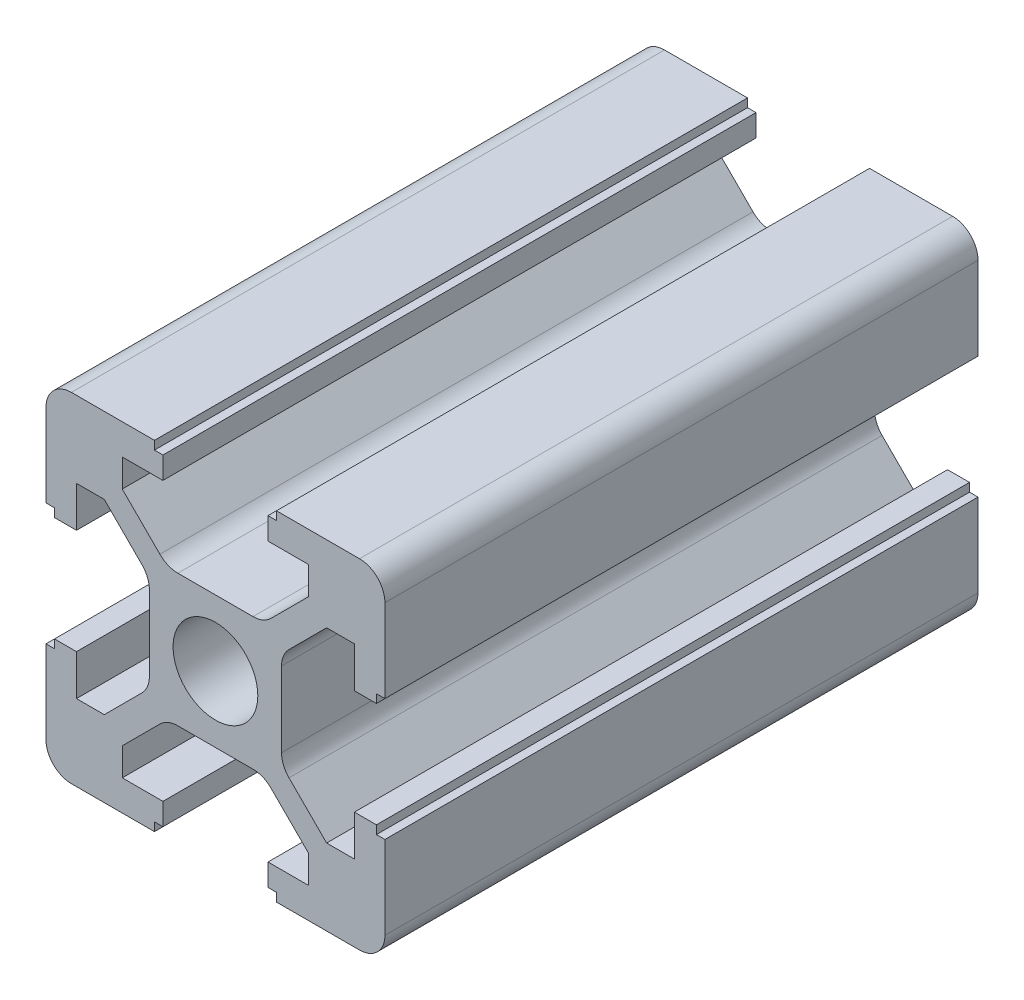
SolidWorks part; units mm, degrees
material "6061 合金"
ref_plane "前视基准面" through (0, 0, 0) normal (0, 0, 1) x (1, 0, 0)
ref_plane "上视基准面" through (0, 0, 0) normal (0, 1, 0) x (1, 0, 0)
ref_plane "右视基准面" through (0, 0, 0) normal (1, 0, 0) x (0, 0, -1)
sketch "草图1" plane through (0, 0, 0) normal (0, 0, 1) x (1, 0, 0)
  line L0 (-6.5607, 5.5) -> (-4.3393, 3.2787)
  line L1 (-3.9, 2.218) -> (-3.9, -2.218)
  line L2 (-4.3393, -3.2787) -> (-6.5607, -5.5)
  line L3 (-6.5607, -5.5) -> (-8.2, -5.5)
  line L4 (-8.2, -5.5) -> (-8.2, -3.1)
  line L5 (-8.2, -3.1) -> (-9.5, -3.1)
  line L6 (-9.5, -3.1) -> (-9.5, -3.6)
  line L7 (-9.5, -3.6) -> (-10, -3.6)
  line L8 (-10, -3.6) -> (-10, -8.5)
  line L9 (-6.5607, 5.5) -> (-8.2, 5.5)
  line L10 (-8.2, 5.5) -> (-8.2, 3.1)
  line L11 (-8.2, 3.1) -> (-9.5, 3.1)
  line L12 (-9.5, 3.1) -> (-9.5, 3.6)
  line L13 (-9.5, 3.6) -> (-10, 3.6)
  line L14 (-10, 3.6) -> (-10, 8.5)
  line L15 (5.5, 6.5607) -> (3.2787, 4.3393)
  line L16 (2.218, 3.9) -> (-2.218, 3.9)
  line L17 (-3.2787, 4.3393) -> (-5.5, 6.5607)
  line L18 (-5.5, 6.5607) -> (-5.5, 8.2)
  line L19 (-5.5, 8.2) -> (-3.1, 8.2)
  line L20 (-3.1, 8.2) -> (-3.1, 9.5)
  line L21 (-3.1, 9.5) -> (-3.6, 9.5)
  line L22 (-3.6, 9.5) -> (-3.6, 10)
  line L23 (-3.6, 10) -> (-8.5, 10)
  line L24 (5.5, 6.5607) -> (5.5, 8.2)
  line L25 (5.5, 8.2) -> (3.1, 8.2)
  line L26 (3.1, 8.2) -> (3.1, 9.5)
  line L27 (3.1, 9.5) -> (3.6, 9.5)
  line L28 (3.6, 9.5) -> (3.6, 10)
  line L29 (3.6, 10) -> (8.5, 10)
  line L30 (6.5607, -5.5) -> (4.3393, -3.2787)
  line L31 (3.9, -2.218) -> (3.9, 2.218)
  line L32 (4.3393, 3.2787) -> (6.5607, 5.5)
  line L33 (6.5607, 5.5) -> (8.2, 5.5)
  line L34 (8.2, 5.5) -> (8.2, 3.1)
  line L35 (8.2, 3.1) -> (9.5, 3.1)
  line L36 (9.5, 3.1) -> (9.5, 3.6)
  line L37 (9.5, 3.6) -> (10, 3.6)
  line L38 (10, 3.6) -> (10, 8.5)
  line L39 (6.5607, -5.5) -> (8.2, -5.5)
  line L40 (8.2, -5.5) -> (8.2, -3.1)
  line L41 (8.2, -3.1) -> (9.5, -3.1)
  line L42 (9.5, -3.1) -> (9.5, -3.6)
  line L43 (9.5, -3.6) -> (10, -3.6)
  line L44 (10, -3.6) -> (10, -8.5)
  line L45 (-5.5, -6.5607) -> (-3.2787, -4.3393)
  line L46 (-2.218, -3.9) -> (2.218, -3.9)
  line L47 (3.2787, -4.3393) -> (5.5, -6.5607)
  line L48 (5.5, -6.5607) -> (5.5, -8.2)
  line L49 (5.5, -8.2) -> (3.1, -8.2)
  line L50 (3.1, -8.2) -> (3.1, -9.5)
  line L51 (3.1, -9.5) -> (3.6, -9.5)
  line L52 (3.6, -9.5) -> (3.6, -10)
  line L53 (3.6, -10) -> (8.5, -10)
  line L54 (-5.5, -6.5607) -> (-5.5, -8.2)
  line L55 (-5.5, -8.2) -> (-3.1, -8.2)
  line L56 (-3.1, -8.2) -> (-3.1, -9.5)
  line L57 (-3.1, -9.5) -> (-3.6, -9.5)
  line L58 (-3.6, -9.5) -> (-3.6, -10)
  line L59 (-3.6, -10) -> (-8.5, -10)
  line L60 (0, 0) -> (-3.9, 2.8393) construction
  line L61 (0, 0) -> (2.8393, 3.9) construction
  arc A0 (4.3393, -3.2787) -> (3.9, -2.218) centre (5.4, -2.218) cw
  arc A1 (3.9, 2.218) -> (4.3393, 3.2787) centre (5.4, 2.218) cw
  arc A2 (3.2787, 4.3393) -> (2.218, 3.9) centre (2.218, 5.4) cw
  arc A3 (-2.218, 3.9) -> (-3.2787, 4.3393) centre (-2.218, 5.4) cw
  arc A4 (-4.3393, 3.2787) -> (-3.9, 2.218) centre (-5.4, 2.218) cw
  arc A5 (-3.9, -2.218) -> (-4.3393, -3.2787) centre (-5.4, -2.218) cw
  arc A6 (2.218, -3.9) -> (3.2787, -4.3393) centre (2.218, -5.4) cw
  arc A7 (-3.2787, -4.3393) -> (-2.218, -3.9) centre (-2.218, -5.4) cw
  arc A8 (-10, -8.5) -> (-8.5, -10) centre (-8.5, -8.5) ccw
  arc A9 (10, -8.5) -> (8.5, -10) centre (8.5, -8.5) cw
  arc A10 (8.5, 10) -> (10, 8.5) centre (8.5, 8.5) cw
  arc A11 (-10, 8.5) -> (-8.5, 10) centre (-8.5, 8.5) cw
  circle A12 centre (0, 0) radius 2.5
  point P27 (-3.9, 0)
  point P75 (2.8393, 3.9)
  dimension "D12" = 1.5
  dimension "D13" = 5
  dimension "D2" = 20
  dimension "D3" = 7.2
  dimension "D4" = 6.2
  dimension "D5" = 7.8
  dimension "D6" = 45
  dimension "D7" = 1.5
  dimension "D8" = 11
  dimension "D9" = 1.8
  dimension "D10" = 0.5
  dimension "D11" = 3.1
  dimension "D1" = 4
extrude "凸台-拉伸1" add sketch "草图1" along normal mid plane 35
